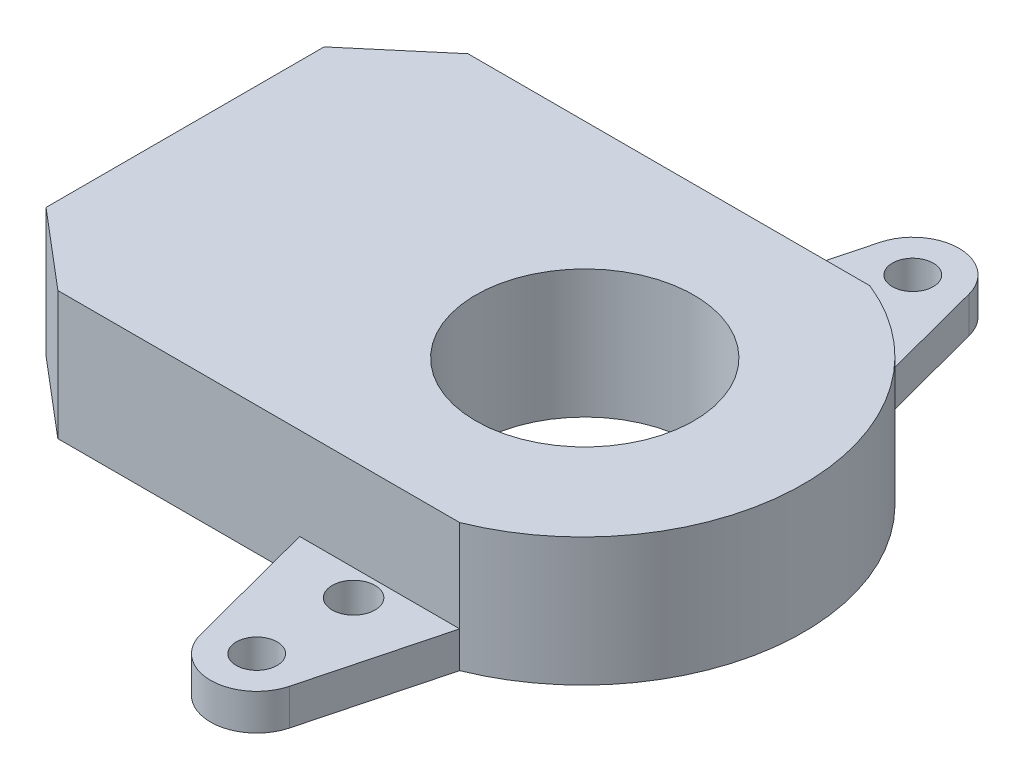
SolidWorks part; units mm, degrees
ref_plane "Front Plane" through (0, 0, 0) normal (0, 0, 1) x (1, 0, 0)
ref_plane "Top Plane" through (0, 0, 0) normal (0, 1, 0) x (1, 0, 0)
ref_plane "Right Plane" through (0, 0, 0) normal (1, 0, 0) x (0, 0, -1)
sketch "Sketch1" plane through (0, 0, 0) normal (0, 1, 0) x (1, 0, 0)
  line L0 (0, -9.7536) -> (0, 9.7536)
  line L1 (0, 9.7536) -> (5.464, 14.385)
  line L2 (5.464, 14.385) -> (33.6525, 14.385)
  line L3 (0, 0) -> (43.38, 0) construction
  line L4 (5.464, -14.385) -> (33.6525, -14.385)
  line L5 (0, -9.7536) -> (5.464, -14.385)
  arc A0 (33.6525, 14.385) -> (43.38, 0) centre (27.88, 0) cw
  arc A1 (33.6525, -14.385) -> (43.38, 0) centre (27.88, 0) ccw
  dimension "D1" = 15.5
  dimension "D2" = 14.385
  dimension "D3" = 43.38
  dimension "D4" = 19.5072
  dimension "D5" = 7.1628
extrude "Boss-Extrude1" add sketch "Sketch1" along normal blind 9
sketch "Sketch2" plane through (0, 0, 0) normal (0, -1, 0) x (1, 0, 0)
  line L0 (33.6525, 14.385) -> (31.1714, 23.8347)
  line L1 (24.9086, 23.8347) -> (22.4275, 14.385)
  line L2 (43.38, 0) -> (0, 0) construction
  line L3 (28.04, 26.25) -> (28.04, 14.385) construction
  line L4 (5.464, 14.385) -> (33.6525, 14.385) construction
  line L5 (0, -9.7536) -> (5.464, -14.385)
  line L6 (5.464, -14.385) -> (33.6525, -14.385)
  line L7 (33.6525, 14.385) -> (5.464, 14.385)
  line L8 (5.464, 14.385) -> (0, 9.7536)
  line L9 (0, 9.7536) -> (0, -9.7536)
  line L10 (0, -9.7536) -> (5.464, -14.385) construction
  line L11 (5.464, -14.385) -> (33.6525, -14.385) construction
  line L12 (33.6525, 14.385) -> (5.464, 14.385) construction
  line L13 (5.464, 14.385) -> (0, 9.7536) construction
  line L14 (0, 9.7536) -> (0, -9.7536) construction
  line L15 (31.1714, 23.8347) -> (33.6525, 14.385)
  line L16 (22.4275, 14.385) -> (24.9086, 23.8347)
  line L17 (33.6525, 14.385) -> (31.1714, 23.8347)
  line L18 (24.9086, 23.8347) -> (22.4275, 14.385)
  line L19 (31.1714, 23.8347) -> (33.6525, 14.385)
  line L20 (22.4275, 14.385) -> (24.9086, 23.8347)
  line L21 (28.04, -26.25) -> (28.04, -14.385) construction
  line L22 (22.4275, -14.385) -> (24.9086, -23.8347)
  line L23 (31.1714, -23.8347) -> (33.6525, -14.385)
  line L24 (24.9086, -23.8347) -> (22.4275, -14.385)
  line L25 (33.6525, -14.385) -> (31.1714, -23.8347)
  line L26 (22.4275, -14.385) -> (24.9086, -23.8347)
  line L27 (31.1714, -23.8347) -> (33.6525, -14.385)
  line L28 (24.9086, -23.8347) -> (22.4275, -14.385)
  line L29 (33.6525, -14.385) -> (31.1714, -23.8347)
  arc A0 (31.1714, 23.8347) -> (24.9086, 23.8347) centre (28.04, 23.0125) ccw
  arc A1 (33.6525, -14.385) -> (33.6525, 14.385) centre (27.88, 0) ccw
  arc A2 (33.6525, -14.385) -> (33.6525, 14.385) centre (27.88, 0) ccw construction
  circle A3 centre (28.04, 23.0125) radius 1.435
  circle A4 centre (28.04, 16.215) radius 1.5
  circle A5 centre (28.04, -16.215) radius 1.5
  circle A6 centre (28.04, -23.0125) radius 1.435
  arc A7 (31.1714, -23.8347) -> (24.9086, -23.8347) centre (28.04, -23.0125) cw
  point P14 (16.6385, 14.385)
  point P20 (0, 0)
  point P21 (0, 0)
  point P22 (0, 0)
  point P23 (0, 0)
  point P24 (26.7761, 28.548)
  point P25 (28.9335, 26.3714)
  point P26 (0, 0)
  point P29 (33.6525, 14.385)
  point P30 (25.7145, 23.8225)
  line M12 (5.464, -14.385) -> (33.6525, -14.385)
  line M14 (33.6525, 14.385) -> (5.464, 14.385)
  dimension "D3" = 2.87
  dimension "D4" = 3
  dimension "D5" = 23.0125
  dimension "D6" = 16.215
  dimension "D2" = 15.34
  dimension "D7" = 26.25
  dimension "D1" = 0
extrude "Boss-Extrude2" add sketch "Sketch2" against normal blind 2.54 contours A7 L23 L22 A5 A6 M12 | L0 A0 L1 A4 A3 M14
sketch "Sketch3" plane through (0, 9, 0) normal (0, 1, 0) x (1, 0, 0)
  line L0 (43.38, 0) -> (0, 0) construction
  line L1 (0, 9.7536) -> (0, -9.7536) construction
  arc A0 (33.6525, -14.385) -> (33.6525, 14.385) centre (27.88, 0) ccw construction
  arc A1 (33.6525, -14.385) -> (33.6525, 14.385) centre (27.88, 0) ccw construction
  circle A2 centre (28.04, 0) radius 7.65
  dimension "D1" = 15.34
  dimension "D2" = 15.3
extrude "Cut-Extrude1" cut sketch "Sketch3" against normal through all
equation "\"D2@Sketch1\"=28.77/2"
equation "\"D4@Sketch1\"=0.768in"
equation "\"D5@Sketch2\"=46.025/2"
equation "\"D6@Sketch2\"=32.43/2"
